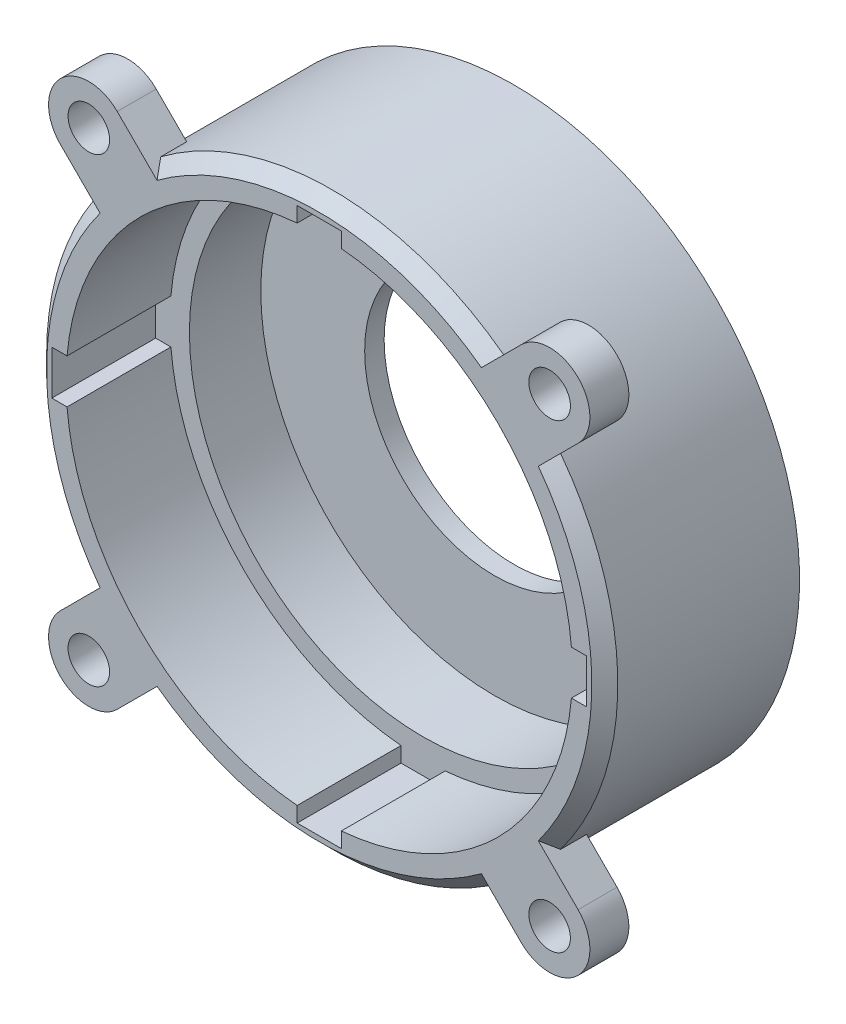
SolidWorks part; units mm, degrees
ref_plane "Front Plane" through (0, 0, 0) normal (0, 0, 1) x (1, 0, 0)
ref_plane "Top Plane" through (0, 0, 0) normal (0, 1, 0) x (1, 0, 0)
ref_plane "Right Plane" through (0, 0, 0) normal (1, 0, 0) x (0, 0, -1)
sketch "Sketch1" plane through (0, 0, 0) normal (0, 0, 1) x (1, 0, 0)
  circle A0 centre (0, 0) radius 22
  dimension "D1" = 44
extrude "Boss-Extrude1" add sketch "Sketch1" along normal mid plane 16.5
sketch "Sketch2" plane through (0, 0, 8.25) normal (0, 0, 1) x (1, 0, 0)
  circle A0 centre (0, 0) radius 18
  dimension "D1" = 36
extrude "Cut-Extrude1" cut sketch "Sketch2" against normal blind 13.5
sketch "Sketch3" plane through (0, 0, 8.25) normal (0, 0, 1) x (1, 0, 0)
  circle A0 centre (0, 0) radius 19.5
  dimension "D1" = 39
extrude "Cut-Extrude2" cut sketch "Sketch3" against normal blind 8
sketch "Sketch4" plane through (0, 0, -8.25) normal (0, 0, -1) x (-1, 0, 0)
  circle A0 centre (0, 0) radius 10
  dimension "D1" = 20
extrude "Cut-Extrude3" cut sketch "Sketch4" against normal through all both and the other way through all
sketch "Sketch6" plane through (0, 0, 8.25) normal (0, 0, 1) x (1, 0, 0)
  line L1 (1.7, 20.6) -> (-1.7, 20.6)
  line L2 (1.7, 20.6) -> (1.7, 18.4)
  line L3 (1.7, 18.4) -> (-1.7, 18.4)
  line L4 (-1.7, 20.6) -> (-1.7, 18.4)
  line L5 (1.7, 20.6) -> (-1.7, 18.4) construction
  line L6 (1.7, 18.4) -> (-1.7, 20.6) construction
  circle A0 centre (0, 0) radius 19.5 construction
  circle A1 centre (0, 0) radius 19.5 construction
  point P0 (0, 19.5)
  dimension "D1" = 2.2
  dimension "D2" = 3.4
extrude "Cut-Extrude5" cut sketch "Sketch6" against normal up to surface (8 mm away) up to face at (19.5, 0, 0.25)
pattern_circular "CirPattern1" count 4 over 360 about axis through (0, 0, 0) along (0, 0, 1) of "Cut-Extrude5"
sketch "Sketch7" plane through (0, 0, -8.25) normal (0, 0, -1) x (-1, 0, 0)
  circle A0 centre (0, 0) radius 22
extrude "Cut-Extrude6" cut sketch "Sketch7" against normal blind 1.5
chamfer "Chamfer1" distance 1 angle 45 1 edges at (22, 0, 8.25)
sketch "Sketch8" plane through (0, 0, 8.25) normal (0, 0, 1) x (1, 0, 0)
  line L1 (15.5563, 19.9404) -> (12.4945, 16.8786)
  line L6 (19.9404, 15.5563) -> (16.8786, 12.4945)
  line L7 (12.4945, 16.8786) -> (16.8786, 12.4945)
  circle A2 centre (17.7484, 17.7484) radius 1.6
  arc A4 (19.9404, 15.5563) -> (15.5563, 19.9404) centre (17.7484, 17.7484) ccw
  circle A6 centre (0, 0) radius 21 construction
  point P9 (0, 0)
extrude "Boss-Extrude2" add sketch "Sketch8" against normal blind 3
pattern_circular "CirPattern2" count 4 over 360 about axis through (0, 0, 0) along (0, 0, 1) of "Boss-Extrude2"
